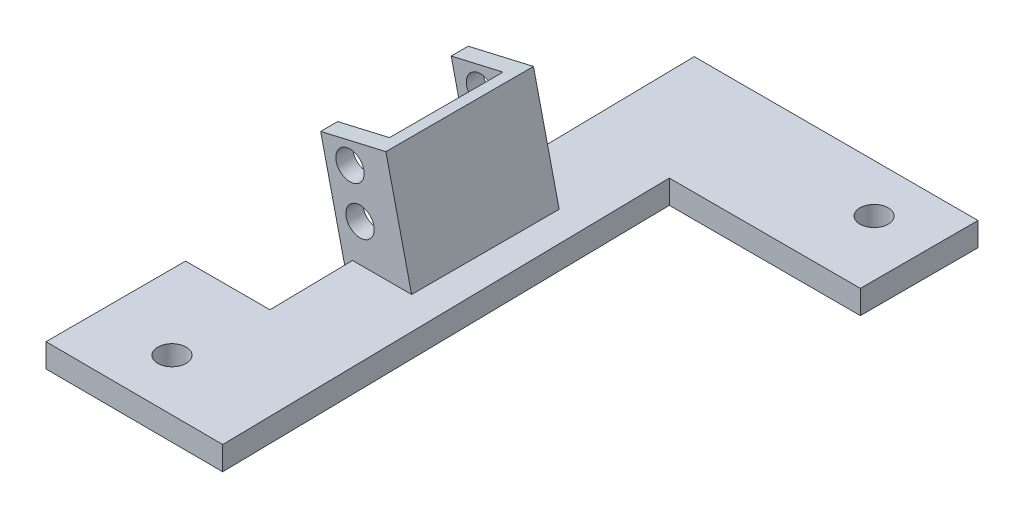
SolidWorks part; units mm, degrees
ref_plane "Front Plane" through (0, 0, 0) normal (0, 0, 1) x (1, 0, 0)
ref_plane "Top Plane" through (0, 0, 0) normal (0, 1, 0) x (1, 0, 0)
ref_plane "Right Plane" through (0, 0, 0) normal (1, 0, 0) x (0, 0, -1)
sketch "Sketch1" plane through (0, 0, 0) normal (0, 0, 1) x (1, 0, 0)
  line L0 (347.1928, 233.3099) -> (352.9388, 208.4948)
  line L1 (338.8256, 231.3724) -> (358.7891, 235.995) construction
  line L2 (352.9388, 208.4948) -> (367.5429, 211.8764)
  line L3 (367.5429, 211.8764) -> (361.7969, 236.6915)
  line L4 (361.7969, 236.6915) -> (347.1928, 233.3099)
  line L5 (338.6024, 208.4556) -> (357.7178, 212.8818) construction
  line L6 (338.6024, 208.4556) -> (357.7178, 212.8818)
  line L7 (352.2179, 211.6083) -> (357.7178, 212.8818)
  arc A0 (361.4826, 228.7505) -> (358.7891, 235.995) centre (353.7541, 230) ccw construction
  arc A1 (361.4826, 228.7505) -> (362.3955, 224.3254) centre (367.7512, 227.737) ccw construction
  arc A2 (362.9827, 217.3077) -> (362.3955, 224.3254) centre (356.0099, 220.2578) ccw construction
  arc A3 (357.7178, 212.8818) -> (362.9827, 217.3077) centre (356.0099, 220.2578) ccw construction
  arc A4 (361.4826, 228.7505) -> (358.7891, 235.995) centre (353.7541, 230) ccw
  arc A5 (361.4826, 228.7505) -> (362.3955, 224.3254) centre (367.7512, 227.737) ccw
  arc A6 (362.9827, 217.3077) -> (362.3955, 224.3254) centre (356.0099, 220.2578) ccw
  arc A7 (357.7178, 212.8818) -> (362.9827, 217.3077) centre (356.0099, 220.2578) ccw
  arc A8 (357.7178, 212.8818) -> (362.9827, 217.3077) centre (356.0099, 220.2578) ccw
  arc A9 (362.9827, 217.3077) -> (362.3955, 224.3254) centre (356.0099, 220.2578) ccw
  arc A10 (362.3955, 224.3254) -> (361.4826, 228.7505) centre (367.7512, 227.737) cw
  arc A11 (361.4826, 228.7505) -> (358.7891, 235.995) centre (353.7541, 230) ccw
extrude "Boss-Extrude1" add sketch "Sketch1" against normal blind 29.21 contours A7 L6 L0 L2 L3 L4 A4 A5 A6
sketch "Sketch2" plane through (0, 0, -29.21) normal (0, 0, -1) x (-1, 0, 0)
  line L0 (-358.7891, 235.995) -> (-347.1928, 233.3099)
  line L1 (-347.1928, 233.3099) -> (-352.2179, 211.6083)
  line L2 (-352.2179, 211.6083) -> (-357.7178, 212.8818)
  arc A0 (-357.7178, 212.8818) -> (-362.3955, 224.3254) centre (-356.0099, 220.2578) cw
  arc A1 (-362.3955, 224.3254) -> (-361.4826, 228.7505) centre (-367.7512, 227.737) ccw
  arc A2 (-361.4826, 228.7505) -> (-358.7891, 235.995) centre (-353.7541, 230) cw
  circle A3 centre (-353.7541, 230) radius 3.175 construction
  circle A4 centre (-356.0099, 220.2578) radius 3.175 construction
  circle A5 centre (-353.7541, 230) radius 3.175
  circle A6 centre (-356.0099, 220.2578) radius 3.175
  circle A7 centre (-356.0099, 220.2578) radius 3.175
  circle A8 centre (-353.7541, 230) radius 3.175
  arc M8 (-357.7178, 212.8818) -> (-362.3955, 224.3254) centre (-356.0099, 220.2578) cw
  arc M9 (-362.3955, 224.3254) -> (-361.4826, 228.7505) centre (-367.7512, 227.737) ccw
  arc M10 (-361.4826, 228.7505) -> (-358.7891, 235.995) centre (-353.7541, 230) cw
  line M15 (-352.2179, 211.6083) -> (-357.7178, 212.8818)
extrude "Boss-Extrude2" add sketch "Sketch2" against normal up to surface (3.81 mm away) contours L1 L0 A6 A5 M10 M9 M8 M15
sketch "Sketch3" plane through (0, 0, 0) normal (0, 0, 1) x (1, 0, 0)
  line L0 (347.1928, 233.3099) -> (352.9388, 208.4948)
  line L1 (352.9388, 208.4948) -> (367.5429, 211.8764)
  line L2 (367.5429, 211.8764) -> (361.7969, 236.6915)
  line L3 (361.7969, 236.6915) -> (347.1928, 233.3099)
  circle A0 centre (356.0099, 220.2578) radius 3.175 construction
  circle A1 centre (353.7541, 230) radius 3.175 construction
  circle A2 centre (356.0099, 220.2578) radius 3.175
  circle A3 centre (353.7541, 230) radius 3.175
  circle A4 centre (353.7541, 230) radius 3.175
  circle A5 centre (356.0099, 220.2578) radius 3.175
  arc M6 (362.3955, 224.3254) -> (357.7178, 212.8818) centre (356.0099, 220.2578) cw
  line M7 (357.7178, 212.8818) -> (352.2179, 211.6083)
  line M8 (352.2179, 211.6083) -> (352.9388, 208.4948)
  line M9 (352.9388, 208.4948) -> (367.5429, 211.8764)
  line M10 (367.5429, 211.8764) -> (361.7969, 236.6915)
  line M11 (361.7969, 236.6915) -> (358.7891, 235.995)
  arc M12 (358.7891, 235.995) -> (361.4826, 228.7505) centre (353.7541, 230) cw
  arc M13 (361.4826, 228.7505) -> (362.3955, 224.3254) centre (367.7512, 227.737) ccw
extrude "Boss-Extrude3" add sketch "Sketch3" along normal blind 3.81 contours L3 L0 A3 A2 M12 M7 M6 M13 | M13 M6 M7 M8 M9 M10 M11 M12
ref_plane "Plane1" through (0, 211.8764, 0) normal (0, 1, 0) x (1, 0, 0)
sketch "Sketch5" plane through (0, 211.8764, 0) normal (0, 1, 0) x (1, 0, 0)
  line L1 (353.0649, 73.9078) -> (416.5649, 73.9078)
  line L6 (416.5649, 73.9078) -> (416.5649, 47.5898)
  line L7 (416.5649, 47.5898) -> (373.8144, 47.5898)
  line L8 (373.8144, 47.5898) -> (375.4776, -54.0102)
  line L9 (335.7799, -53.8514) -> (335.7799, -22.6122)
  line L10 (335.7799, -22.6122) -> (354.645, -22.6122)
  line L11 (354.645, -22.6122) -> (353.0649, 73.9078)
  line L12 (335.7799, -53.8514) -> (375.4776, -54.0102)
  circle A0 centre (404.0733, 63.1493) radius 3.175
  circle A1 centre (352.4976, -42.3935) radius 3.175
  circle A2 centre (352.4976, -42.3935) radius 3.175 construction
  point P1 (0, 0)
  point P3 (352.4976, -42.3935)
  point P9 (0, 0)
  point P19 (0, 0)
  point P21 (417.4435, 74.9168)
  point P22 (0, 0)
  dimension "D1" = 6.35
  dimension "D6" = 6.35
  dimension "D2" = 96.52
  dimension "D3" = 101.6
  dimension "D4" = 63.5
  dimension "D5" = 31.2392
  dimension "D7" = 11.5246
  dimension "D8" = 16.7177
  dimension "D9" = 7.112
  dimension "D10" = 20.3159
  dimension "D11" = 270
extrude "Boss-Extrude4" add sketch "Sketch5" against normal blind 5.2893 contours L1 L6 L7 L8 L12 L9 L10 L11
